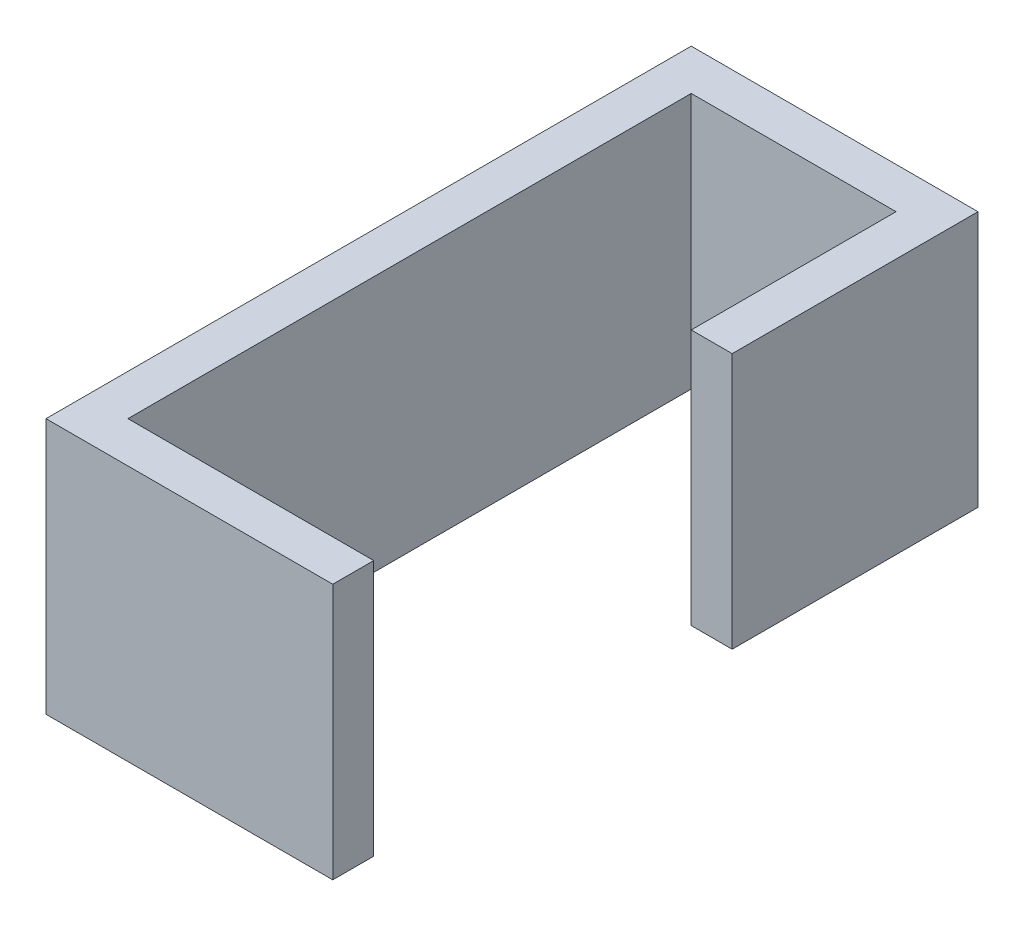
SolidWorks part; units mm, degrees
ref_plane "Front Plane" through (0, 0, 0) normal (0, 0, 1) x (1, 0, 0)
ref_plane "Top Plane" through (0, 0, 0) normal (0, 1, 0) x (1, 0, 0)
ref_plane "Right Plane" through (0, 0, 0) normal (1, 0, 0) x (0, 0, -1)
sketch "Sketch1" plane through (0, 0, 0) normal (0, 1, 0) x (1, 0, 0)
  line L0 (0, 0) -> (0, 63)
  line L1 (0, 63) -> (28, 63)
  line L2 (28, 63) -> (28, 39)
  line L3 (28, 39) -> (24, 39)
  line L4 (24, 39) -> (24, 59)
  line L5 (24, 59) -> (4, 59)
  line L6 (4, 59) -> (4, 4)
  line L7 (4, 4) -> (28, 4)
  line L8 (28, 4) -> (28, 0)
  line L9 (28, 0) -> (0, 0)
  dimension "D1" = 55
  dimension "D2" = 20
  dimension "D3" = 4
  dimension "D4" = 4
  dimension "D5" = 20
  dimension "D6" = 24
  dimension "D7" = 4
  dimension "D8" = 4
extrude "Boss-Extrude1" add sketch "Sketch1" along normal blind 25
